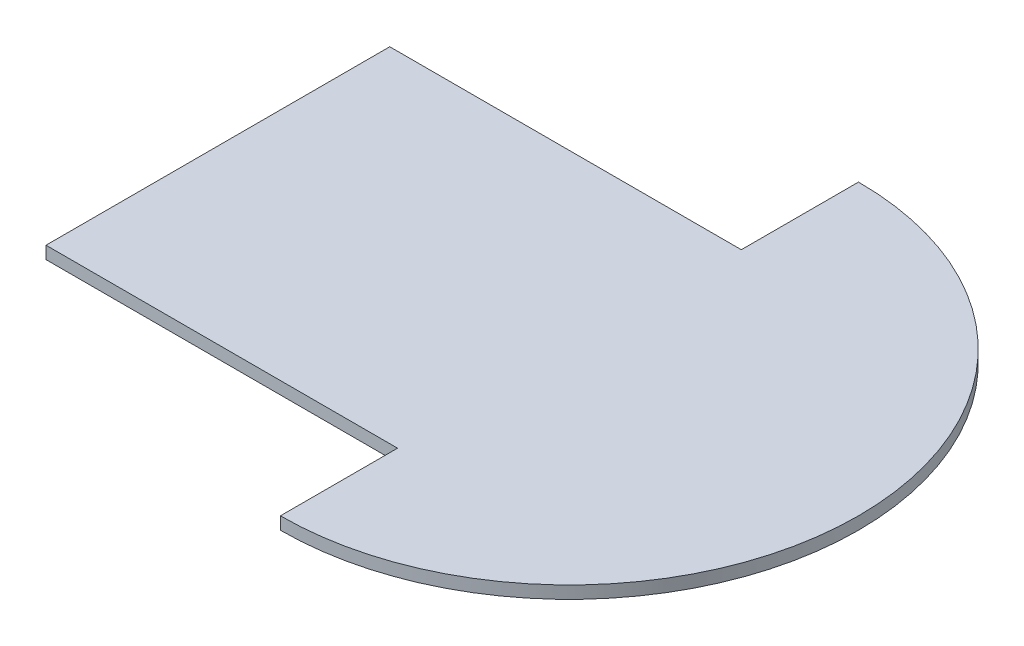
SolidWorks part; units mm, degrees
other "Markup1"
sketch "Sketch2" plane through (-15.8817, 1.6, 18.964) normal (0.4, 0.515, 0.7581) x (0.8844, 0, -0.4667)
ref_plane "Front Plane" through (0, 0, 0) normal (0, 0, 1) x (1, 0, 0)
ref_plane "Top Plane" through (0, 0, 0) normal (0, 1, 0) x (1, 0, 0)
ref_plane "Right Plane" through (0, 0, 0) normal (1, 0, 0) x (0, 0, -1)
sketch "Sketch1" plane through (0, 0, 0) normal (0, 1, 0) x (1, 0, 0)
  line L0 (-81.7187, 33.036) -> (-81.7187, -10.964)
  line L1 (-81.7187, 33.036) -> (-36.7187, 33.036)
  line L2 (-36.7187, 33.036) -> (-36.7187, 48.036)
  line L3 (-81.7187, -10.964) -> (-36.7187, -10.964)
  line L4 (-36.7187, -10.964) -> (-36.7187, -25.964)
  arc A0 (-36.7187, 48.036) -> (-36.7187, -25.964) centre (-36.7187, 11.036) cw
  dimension "D1" = 44
  dimension "D2" = 15
  dimension "D3" = 15
  dimension "D4" = 45
  dimension "D5" = 45
extrude "Boss-Extrude1" add sketch "Sketch1" along normal blind 1.6
